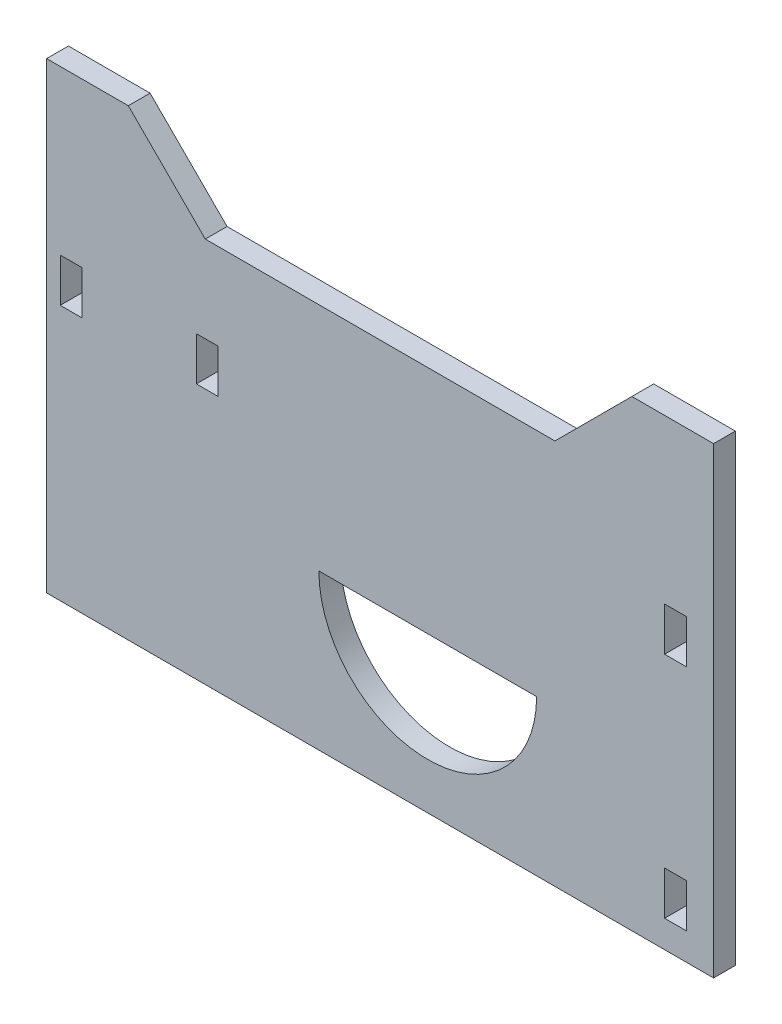
SolidWorks part; units mm, degrees
ref_plane "Front Plane" through (0, 0, 0) normal (0, 0, 1) x (1, 0, 0)
ref_plane "Top Plane" through (0, 0, 0) normal (0, 1, 0) x (1, 0, 0)
ref_plane "Right Plane" through (0, 0, 0) normal (1, 0, 0) x (0, 0, -1)
sketch "Sketch1" plane through (0, 0, 0) normal (0, 0, 1) x (1, 0, 0)
  line L0 (-20, -1.4984) -> (20, -1.4984)
  line L6 (-42.5, 25) -> (-38.5, 25)
  line L9 (-42.5, 25) -> (-42.5, 17)
  line L12 (-42.5, 17) -> (-38.5, 17)
  line L15 (-38.5, 25) -> (-38.5, 17)
  line L51 (52.5, 30) -> (52.5, -30)
  line L54 (43.5, 25) -> (47.5, 25)
  line L55 (43.5, 25) -> (43.5, 17)
  line L56 (43.5, 17) -> (47.5, 17)
  line L57 (47.5, 25) -> (47.5, 17)
  line L58 (47.5, -17) -> (43.5, -17)
  line L59 (47.5, -17) -> (47.5, -25)
  line L60 (47.5, -25) -> (43.5, -25)
  line L61 (43.5, -17) -> (43.5, -25)
  line L65 (-67.5, 25) -> (-63.5, 25)
  line L66 (-67.5, 25) -> (-67.5, 17)
  line L67 (-67.5, 17) -> (-63.5, 17)
  line L68 (-63.5, 25) -> (-63.5, 17)
  line L73 (-70, 30) -> (-70, -30) construction
  line L75 (-70, -30) -> (52.5, -30) construction
  line L76 (52.5, 30) -> (-70, 30)
  line L79 (-70, 30) -> (-70, -30)
  line L80 (-70, -30) -> (52.5, -30)
  arc A12 (-20, -1.4984) -> (20, -1.4984) centre (0, -1.4984) ccw
  point P0 (0, 0)
  point P4 (-65.5, 17)
  point P13 (-38.5, 21)
  point P14 (52.5, 0)
  point P25 (-63.5, 21)
  dimension "D3" = 4
  dimension "D4" = 8
  dimension "D5" = 21
  dimension "D6" = 60
  dimension "D7" = 5
  dimension "D2" = 82
  dimension "D8" = 20
  dimension "D9" = 20
  dimension "D11" = 5
  dimension "D13" = 5
  dimension "D14" = 2.5
  dimension "D15" = 8
  dimension "D16" = 4
  dimension "D18" = 5
extrude "Boss-Extrude1" add sketch "Sketch1" along normal blind 4
sketch "Sketch2" plane through (0, 0, 0) normal (0, 0, 1) x (1, 0, 0)
  line L0 (-70, 30) -> (52.5, 30)
  line L4 (23.3579, 40.8579) -> (-40.8579, 40.8579)
  line L5 (-40.8579, 40.8579) -> (-55, 55)
  line L6 (-55, 55) -> (-70, 55)
  line L7 (-70, 55) -> (-70, 30)
  line L8 (23.3579, 40.8579) -> (37.5, 55)
  line L9 (37.5, 55) -> (52.5, 55)
  line L10 (52.5, 55) -> (52.5, 30)
  line L11 (-70, 30) -> (-70, -30) construction
  point P4 (0, 0)
  dimension "D1" = 25
  dimension "D2" = 20
  dimension "D3" = 15
  dimension "D4" = 135
extrude "Boss-Extrude2" add sketch "Sketch2" along normal blind 4
